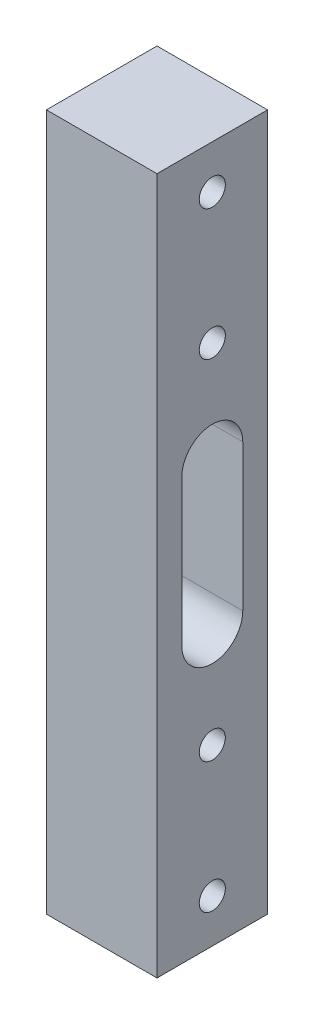
SolidWorks part; units mm, degrees
ref_plane "Front Plane" through (0, 0, 0) normal (0, 0, 1) x (1, 0, 0)
ref_plane "Top Plane" through (0, 0, 0) normal (0, 1, 0) x (1, 0, 0)
ref_plane "Right Plane" through (0, 0, 0) normal (1, 0, 0) x (0, 0, -1)
ref_plane "Plane1" through (293.1364, 622.0489, -296.0531) normal (-1, 0, 0) x (0, 0, 1)
sketch "Sketch1" plane through (293.1364, 622.0489, -296.0531) normal (-1, 0, 0) x (0, 0, 1)
  line L0 (-165.5779, 189.3701) -> (-165.5779, 161.2754) construction
  line L1 (-171.9279, 189.3701) -> (-159.2279, 189.3701)
  line L2 (-171.9279, 189.3701) -> (-171.9279, 109.3701)
  line L3 (-171.9279, 109.3701) -> (-159.2279, 109.3701)
  line L4 (-159.2279, 189.3701) -> (-159.2279, 109.3701)
  line L5 (-162.0779, 157.7754) -> (-162.0779, 140.9649)
  line L6 (-162.0779, 149.3701) -> (-159.2279, 149.3701) construction
  line L7 (-169.0779, 157.7754) -> (-169.0779, 140.9649)
  line L8 (-165.5779, 137.4649) -> (-165.5779, 109.3701) construction
  circle A1 centre (-165.5779, 169.3701) radius 1.5
  circle A2 centre (-165.5779, 184.3701) radius 1.5
  circle A4 centre (-165.5779, 114.3701) radius 1.5
  circle A5 centre (-165.5779, 129.3701) radius 1.5
  arc A6 (-162.0779, 157.7754) -> (-169.0779, 157.7754) centre (-165.5779, 157.7754) ccw
  arc A7 (-169.0779, 140.9649) -> (-162.0779, 140.9649) centre (-165.5779, 140.9649) ccw
  dimension "D1" = 15
  dimension "D2" = 5
  dimension "D5" = 3
  dimension "D6" = 3
  dimension "D7" = 15
  dimension "D8" = 5
  dimension "D10" = 7
  dimension "D3" = 80
  dimension "D4" = 12.7
extrude "Boss-Extrude1" add sketch "Sketch1" along normal blind 12.7
